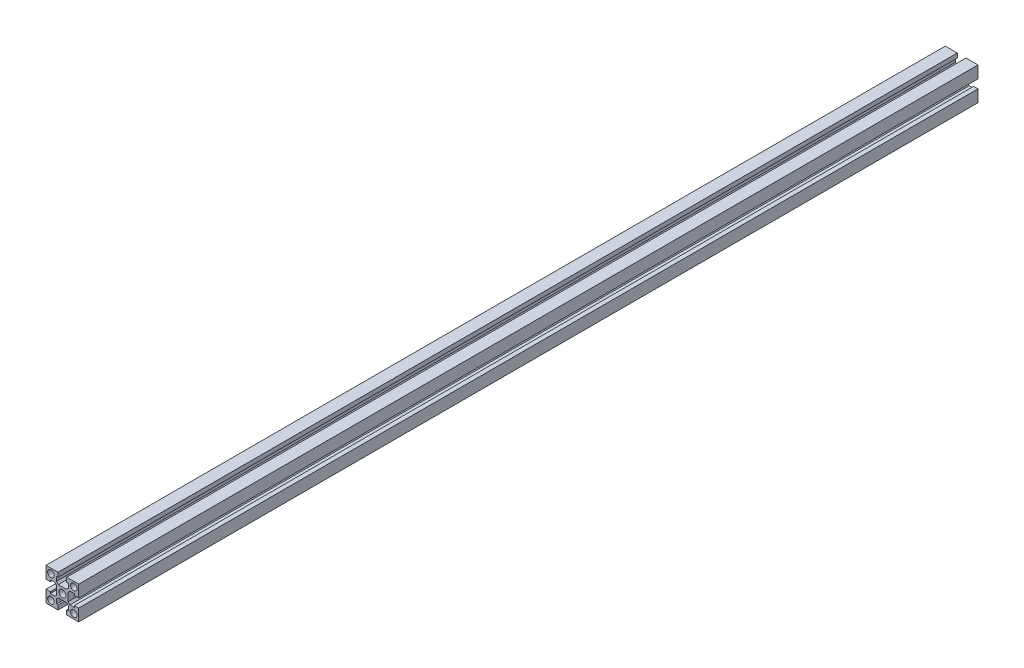
SolidWorks part; units mm, degrees
ref_plane "정면" through (0, 0, 0) normal (0, 0, 1) x (1, 0, 0)
ref_plane "윗면" through (0, 0, 0) normal (0, 1, 0) x (1, 0, 0)
ref_plane "우측면" through (0, 0, 0) normal (1, 0, 0) x (0, 0, -1)
sketch "스케치1" plane through (0, 0, 0) normal (0, 0, 1) x (1, 0, 0)
  line L0 (-10, -10) -> (-2.65, -10)
  line L1 (2.65, -10) -> (10, -10)
  line L2 (10, -10) -> (10, -2.65)
  line L3 (10, 2.65) -> (10, 10)
  line L4 (10, 10) -> (2.65, 10)
  line L5 (-2.65, 10) -> (-10, 10)
  line L6 (-10, 10) -> (-10, 2.65)
  line L7 (-10, -2.65) -> (-10, -10)
  line L8 (0, 10) -> (0, -10) construction
  line L9 (-10, 0) -> (10, 0) construction
  line L10 (2.65, 10) -> (2.65, 7.35)
  line L11 (-2.65, 10) -> (-2.65, 7.35)
  line L12 (-2.5101, 3.5) -> (0, 3.5)
  line L13 (-2.65, 7.35) -> (-3.65, 7.35)
  line L14 (-3.65, 7.35) -> (-3.65, 4.6399)
  line L15 (2.65, 7.35) -> (3.65, 7.35)
  line L16 (2.65, -10) -> (2.65, -7.35)
  line L17 (-2.65, -10) -> (-2.65, -7.35)
  line L18 (0, -3.5) -> (2.5101, -3.5)
  line L19 (-2.65, -7.35) -> (-3.65, -7.35)
  line L20 (2.65, -7.35) -> (3.65, -7.35)
  line L21 (3.65, -7.35) -> (3.65, -4.6399)
  line L22 (-10, 2.65) -> (-7.35, 2.65)
  line L23 (-10, -2.65) -> (-7.35, -2.65)
  line L24 (-3.5, 0) -> (-3.5, 2.5101)
  line L25 (-7.35, -2.65) -> (-7.35, -3.65)
  line L26 (-7.35, 2.65) -> (-7.35, 3.65)
  line L27 (-7.35, 3.65) -> (-4.6399, 3.65)
  line L28 (10, 2.65) -> (7.35, 2.65)
  line L29 (10, -2.65) -> (7.35, -2.65)
  line L30 (3.5, -2.5101) -> (3.5, 0)
  line L31 (7.35, -2.65) -> (7.35, -3.65)
  line L32 (7.35, -3.65) -> (4.6399, -3.65)
  line L33 (7.35, 2.65) -> (7.35, 3.65)
  line L34 (2.5101, -3.5) -> (3.65, -4.6399)
  line L35 (-4.6399, 3.65) -> (-3.5, 2.5101)
  line L36 (-3.65, 4.6399) -> (-2.5101, 3.5)
  line L37 (3.5, -2.5101) -> (4.6399, -3.65)
  line L38 (-2.5101, -3.5) -> (0, -3.5)
  line L39 (-2.65, -7.35) -> (-3.65, -7.35)
  line L40 (-3.65, -7.35) -> (-3.65, -4.6399)
  line L41 (0, 3.5) -> (2.5101, 3.5)
  line L42 (2.65, 7.35) -> (3.65, 7.35)
  line L43 (3.65, 7.35) -> (3.65, 4.6399)
  line L44 (-3.5, 0) -> (-3.5, -2.5101)
  line L45 (-7.35, -2.65) -> (-7.35, -3.65)
  line L46 (-7.35, -3.65) -> (-4.6399, -3.65)
  line L47 (3.5, 2.5101) -> (3.5, 0)
  line L48 (7.35, 2.65) -> (7.35, 3.65)
  line L49 (7.35, 3.65) -> (4.6399, 3.65)
  line L50 (2.5101, 3.5) -> (3.65, 4.6399)
  line L51 (-4.6399, -3.65) -> (-3.5, -2.5101)
  line L52 (-3.65, -4.6399) -> (-2.5101, -3.5)
  line L53 (3.5, 2.5101) -> (4.6399, 3.65)
  circle A0 centre (-7, 7) radius 2
  circle A1 centre (0, 0) radius 2.15
  circle A2 centre (7, 7) radius 2
  circle A3 centre (-7, -7) radius 2
  circle A4 centre (7, -7) radius 2
extrude "보스-돌출1" add sketch "스케치1" along normal mid plane 550 contours L47 L53 L49 L33 L28 L3 L4 L10 L15 L43 L50 L41 L12 L36 L14 L13 L11 L5 L6 L22 L26 L27 L35 L24 L44 L51 L46 L25 L23 L7 L0 L17 L19 L40 L52 L38 L18 L34 L21 L20 L16 L1 L2 L29 L31 L32 L37 L30 A4
